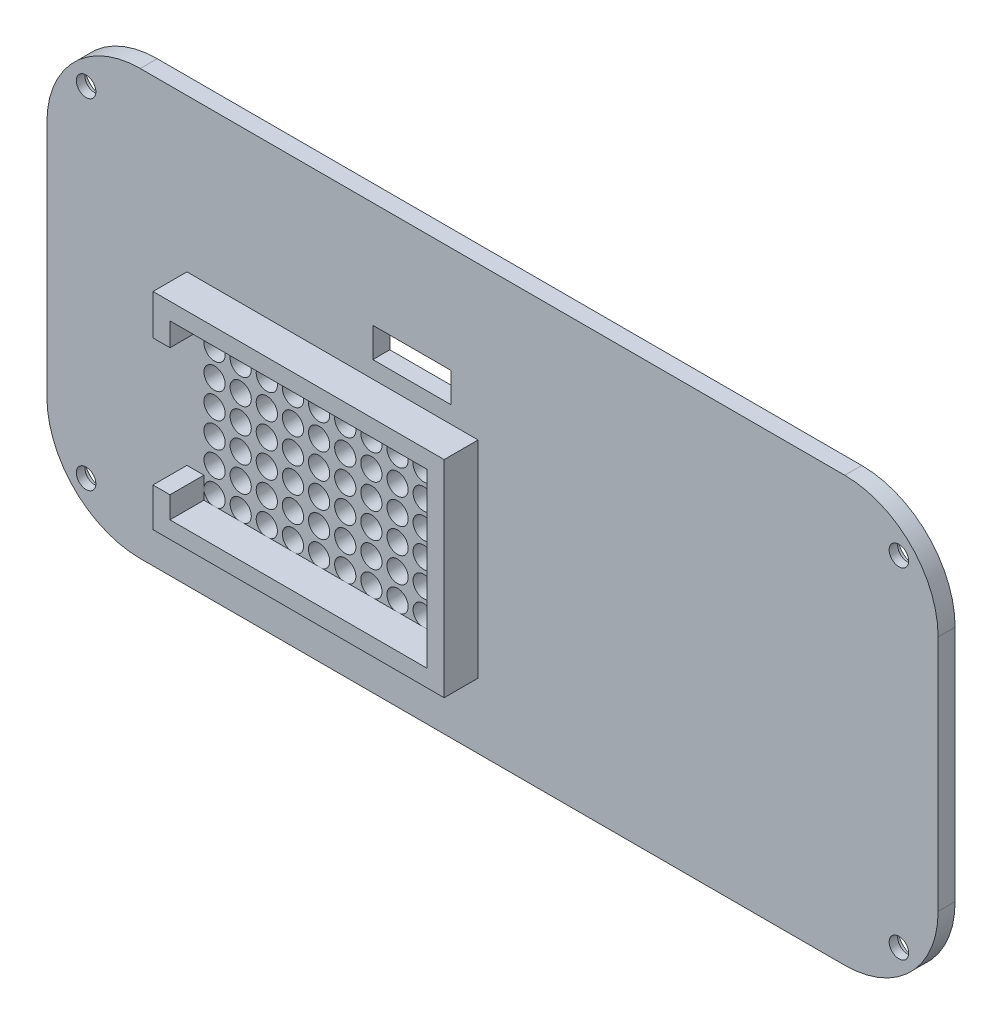
SolidWorks part; units mm, degrees
ref_plane "前视基准面" through (0, 0, 0) normal (0, 0, 1) x (1, 0, 0)
ref_plane "上视基准面" through (0, 0, 0) normal (0, 1, 0) x (1, 0, 0)
ref_plane "右视基准面" through (0, 0, 0) normal (1, 0, 0) x (0, 0, -1)
other "Configuration Table"
sketch "草图1" plane through (0, 0, 0) normal (0, 0, 1) x (1, 0, 0)
  line L1 (-52.5, -25) -> (52.5, -25)
  line L2 (-52.5, -25) -> (-52.5, 25)
  line L3 (-52.5, 25) -> (52.5, 25)
  line L4 (52.5, -25) -> (52.5, 25)
  line L5 (0, 25) -> (0, -25) construction
  line L6 (-52.5, 0) -> (52.5, 0) construction
  point P0 (0, 0)
  dimension "D1" = 105
  dimension "D2" = 50
extrude "凸台-拉伸1" add sketch "草图1" along normal blind 2
fillet "圆角1" radius 11 4 edges at (-52.5, -25, 1) (52.5, -25, 1) (52.5, 25, 1) (-52.5, 25, 1)
sketch "草图3" plane through (0, 0, 0) normal (0, 0, -1) x (-1, 0, 0)
  circle A1 centre (47.8808, -20) radius 2.15
  circle A2 centre (47.8808, 20) radius 2.15
  circle A3 centre (-47.8808, 20) radius 2.15
  circle A4 centre (-47.8808, -20) radius 2.15
  dimension "D1" = 4.3
extrude "切除-拉伸1" cut sketch "草图3" against normal blind 1
sketch "草图4" plane through (0, 0, 1) normal (0, 0, -1) x (-1, 0, 0)
  circle A0 centre (47.8808, -20) radius 1.15
  circle A1 centre (-47.8808, -20) radius 1.15
  circle A2 centre (47.8808, 20) radius 1.15
  circle A3 centre (-47.8808, 20) radius 1.15
  circle A4 centre (-47.8808, 20) radius 2.15 construction
  circle A5 centre (47.8808, 20) radius 2.15 construction
  dimension "D1" = 2.3
extrude "切除-拉伸2" cut sketch "草图4" against normal up to next
sketch "草图5" plane through (0, 0, 0) normal (0, 0, -1) x (-1, 0, 0)
  line L0 (49.5, -3) -> (49.5, 11) construction
  line L1 (14.1, 9) -> (4.9, 9)
  line L2 (14.1, 9) -> (14.1, 12.5)
  line L3 (14.1, 12.5) -> (4.9, 12.5)
  line L4 (4.9, 9) -> (4.9, 12.5)
  line L5 (9.5, 12.5) -> (9.5, 9) construction
  line L6 (14.1, 10.75) -> (4.9, 10.75) construction
  line L8 (38.5, 22) -> (-38.5, 22) construction
  point P0 (9.5, 10.75)
  dimension "D1" = 35.4
  dimension "D2" = 9.5
  dimension "D3" = 3.5
  dimension "D4" = 9.2
extrude "切除-拉伸3" cut sketch "草图5" against normal up to next
sketch "草图6" plane through (0, 0, 2) normal (0, 0, 1) x (1, 0, 0)
  line L0 (41.5, 25) -> (-41.5, 25) construction
  line L1 (-34, 5) -> (-3.7, 5)
  line L2 (-34, 5) -> (-34, -15.3)
  line L3 (-34, -15.3) -> (-3.7, -15.3)
  line L4 (-3.7, 5) -> (-3.7, -15.3)
  dimension "D1" = 20.3
  dimension "D2" = 30.3
  dimension "D3" = 34
  dimension "D4" = 20
extrude "拉伸-薄壁1" add sketch "草图6" along normal blind 4 thin thin type one direction wall 2
sketch "草图7" plane through (0, 0, 2) normal (0, 0, 1) x (1, 0, 0)
  line L0 (-3.7, 5) -> (-34, 5) construction
  line L2 (-34, 5) -> (-34, -15.3) construction
  circle A0 centre (-32.75, 3.75) radius 1.25
  circle A1 centre (-29.67, 3.75) radius 1.25
  circle A2 centre (-26.59, 3.75) radius 1.25
  circle A3 centre (-23.51, 3.75) radius 1.25
  circle A4 centre (-20.43, 3.75) radius 1.25
  circle A5 centre (-17.35, 3.75) radius 1.25
  circle A6 centre (-14.27, 3.75) radius 1.25
  circle A7 centre (-11.19, 3.75) radius 1.25
  circle A8 centre (-8.11, 3.75) radius 1.25
  circle A9 centre (-5.03, 3.75) radius 1.25
  circle A10 centre (-29.67, 0.77) radius 1.25
  circle A11 centre (-26.59, 0.77) radius 1.25
  circle A12 centre (-23.51, 0.77) radius 1.25
  circle A13 centre (-20.43, 0.77) radius 1.25
  circle A14 centre (-17.35, 0.77) radius 1.25
  circle A15 centre (-14.27, 0.77) radius 1.25
  circle A16 centre (-11.19, 0.77) radius 1.25
  circle A17 centre (-8.11, 0.77) radius 1.25
  circle A18 centre (-5.03, 0.77) radius 1.25
  circle A19 centre (-29.67, -2.21) radius 1.25
  circle A20 centre (-26.59, -2.21) radius 1.25
  circle A21 centre (-23.51, -2.21) radius 1.25
  circle A22 centre (-20.43, -2.21) radius 1.25
  circle A23 centre (-17.35, -2.21) radius 1.25
  circle A24 centre (-14.27, -2.21) radius 1.25
  circle A25 centre (-11.19, -2.21) radius 1.25
  circle A26 centre (-8.11, -2.21) radius 1.25
  circle A27 centre (-5.03, -2.21) radius 1.25
  circle A28 centre (-29.67, -5.19) radius 1.25
  circle A29 centre (-26.59, -5.19) radius 1.25
  circle A30 centre (-23.51, -5.19) radius 1.25
  circle A31 centre (-20.43, -5.19) radius 1.25
  circle A32 centre (-17.35, -5.19) radius 1.25
  circle A33 centre (-14.27, -5.19) radius 1.25
  circle A34 centre (-11.19, -5.19) radius 1.25
  circle A35 centre (-8.11, -5.19) radius 1.25
  circle A36 centre (-5.03, -5.19) radius 1.25
  circle A37 centre (-29.67, -8.17) radius 1.25
  circle A38 centre (-26.59, -8.17) radius 1.25
  circle A39 centre (-23.51, -8.17) radius 1.25
  circle A40 centre (-20.43, -8.17) radius 1.25
  circle A41 centre (-17.35, -8.17) radius 1.25
  circle A42 centre (-14.27, -8.17) radius 1.25
  circle A43 centre (-11.19, -8.17) radius 1.25
  circle A44 centre (-8.11, -8.17) radius 1.25
  circle A45 centre (-5.03, -8.17) radius 1.25
  circle A46 centre (-29.67, -11.15) radius 1.25
  circle A47 centre (-26.59, -11.15) radius 1.25
  circle A48 centre (-23.51, -11.15) radius 1.25
  circle A49 centre (-20.43, -11.15) radius 1.25
  circle A50 centre (-17.35, -11.15) radius 1.25
  circle A51 centre (-14.27, -11.15) radius 1.25
  circle A52 centre (-11.19, -11.15) radius 1.25
  circle A53 centre (-8.11, -11.15) radius 1.25
  circle A54 centre (-5.03, -11.15) radius 1.25
  circle A55 centre (-29.67, -14.13) radius 1.25
  circle A56 centre (-26.59, -14.13) radius 1.25
  circle A57 centre (-23.51, -14.13) radius 1.25
  circle A58 centre (-20.43, -14.13) radius 1.25
  circle A59 centre (-17.35, -14.13) radius 1.25
  circle A60 centre (-14.27, -14.13) radius 1.25
  circle A61 centre (-11.19, -14.13) radius 1.25
  circle A62 centre (-8.11, -14.13) radius 1.25
  circle A63 centre (-5.03, -14.13) radius 1.25
  circle A64 centre (-32.75, 0.77) radius 1.25
  circle A65 centre (-32.75, -2.21) radius 1.25
  circle A66 centre (-32.75, -5.19) radius 1.25
  circle A67 centre (-32.75, -8.17) radius 1.25
  circle A68 centre (-32.75, -11.15) radius 1.25
  circle A69 centre (-32.75, -14.13) radius 1.25
  dimension "D1" = 2.5
  dimension "D4" = 3.08
  dimension "D5" = 2.98
  dimension "D2" = 10
  dimension "D3" = 7
extrude "切除-拉伸4" cut sketch "草图7" against normal up to surface (2 mm away) up to face at (-9.5, 10.75, 0)
sketch "草图8" plane through (0, 0, 6) normal (0, 0, 1) x (1, 0, 0)
  line L0 (-34, 3.75) -> (-34, 0.77) construction
  line L1 (-34, 2.26) -> (-36, 2.26)
  line L2 (-34, 2.26) -> (-34, -12.74)
  line L3 (-34, -12.74) -> (-36, -12.74)
  line L4 (-36, 2.26) -> (-36, -12.74)
  line L5 (-36, 7) -> (-36, -17.3) construction
  dimension "D1" = 15
extrude "切除-拉伸5" cut sketch "草图8" against normal up to surface (4 mm away) up to face at (-9.5, 10.75, 2)
